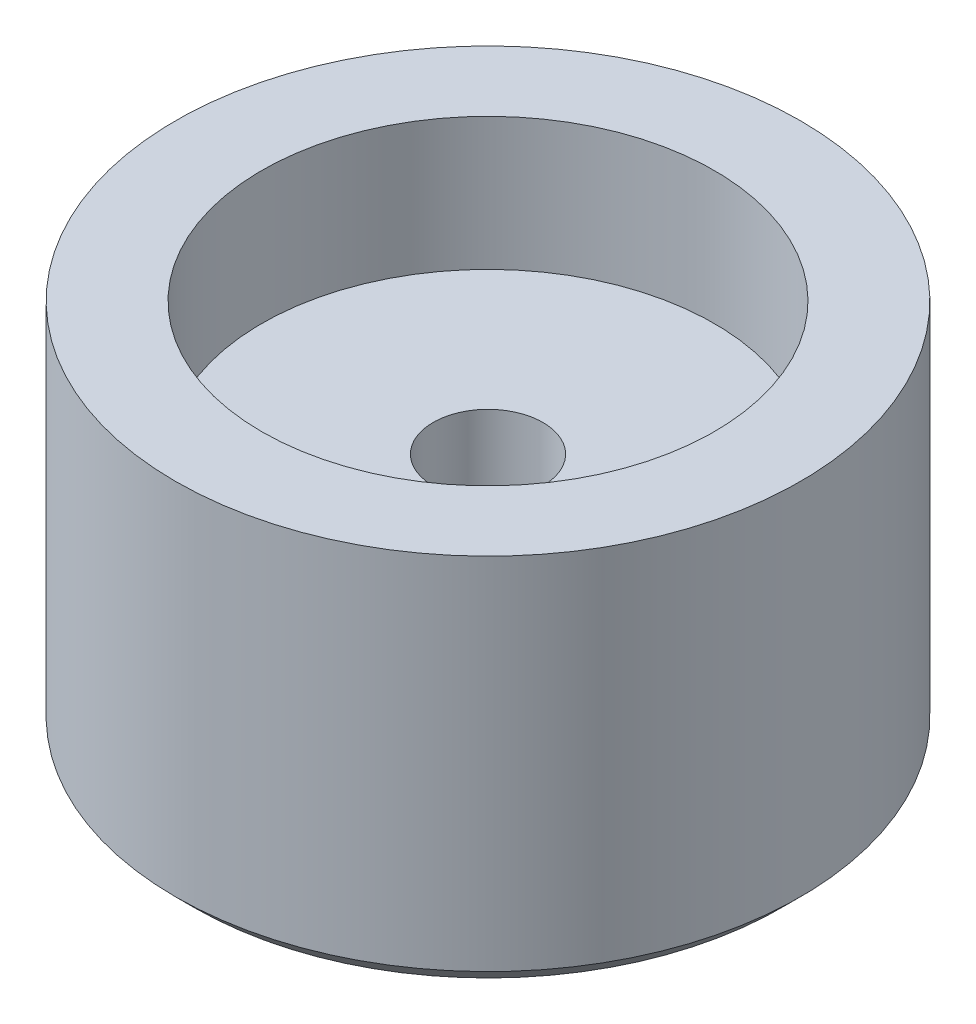
SolidWorks part; units mm, degrees
ref_plane "Front Plane" through (0, 0, 0) normal (0, 0, 1) x (1, 0, 0)
ref_plane "Top Plane" through (0, 0, 0) normal (0, 1, 0) x (1, 0, 0)
ref_plane "Right Plane" through (0, 0, 0) normal (1, 0, 0) x (0, 0, -1)
sketch "Sketch1" plane through (0, 0, 0) normal (0, 1, 0) x (1, 0, 0)
  circle A0 centre (0, 0) radius 8.25
  circle A1 centre (0, 0) radius 1.45
  dimension "D1" = 2.9
  dimension "D2" = 16.5
extrude "Boss-Extrude1" add sketch "Sketch1" along normal blind 10
sketch "Sketch2" plane through (0, 10, 0) normal (0, 1, 0) x (1, 0, 0)
  circle A0 centre (0, 0) radius 5.975
  dimension "D1" = 11.95
extrude "Cut-Extrude1" cut sketch "Sketch2" against normal blind 3.5
chamfer "Chamfer1" distance 0.5 angle 45 1 edges at (0, 0, 8.25)
